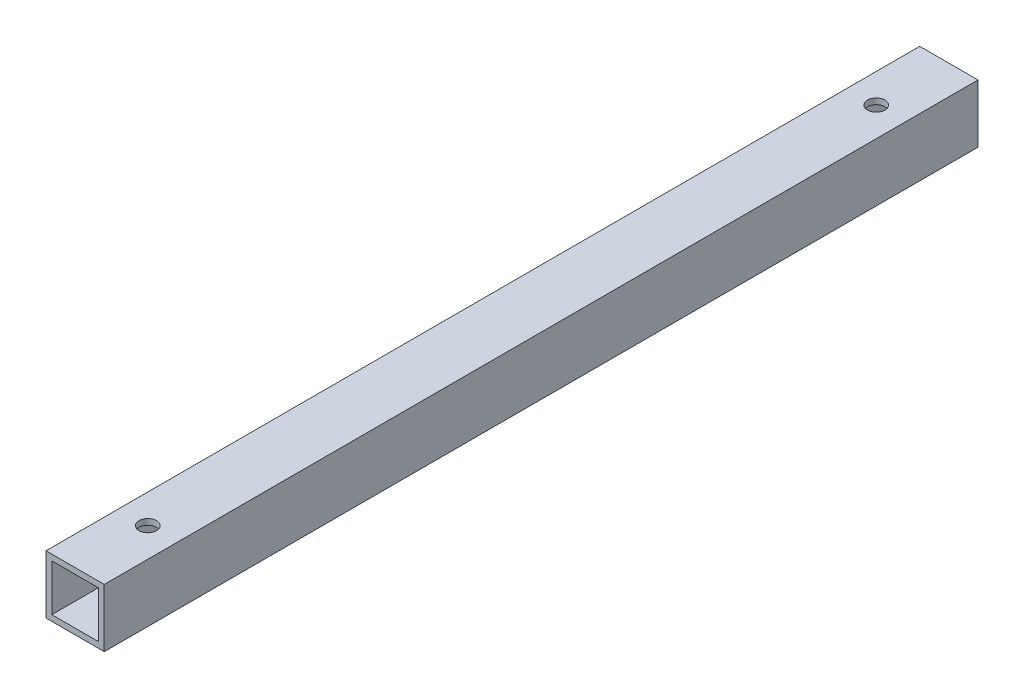
SolidWorks part; units mm, degrees
material "Thornel Mat VMA"
ref_plane "前视基准面" through (0, 0, 0) normal (0, 0, 1) x (1, 0, 0)
ref_plane "上视基准面" through (0, 0, 0) normal (0, 1, 0) x (1, 0, 0)
ref_plane "右视基准面" through (0, 0, 0) normal (1, 0, 0) x (0, 0, -1)
sketch "草图1" plane through (0, 0, 0) normal (0, 0, 1) x (1, 0, 0)
  line L1 (5, 5) -> (-5, 5)
  line L2 (5, 5) -> (5, -5)
  line L3 (5, -5) -> (-5, -5)
  line L4 (-5, 5) -> (-5, -5)
  line L5 (5, 5) -> (-5, -5) construction
  line L6 (5, -5) -> (-5, 5) construction
  line L7 (4, 4) -> (-4, 4)
  line L8 (4, 4) -> (4, -4)
  line L9 (4, -4) -> (-4, -4)
  line L10 (-4, 4) -> (-4, -4)
  line L11 (4, 4) -> (-4, -4) construction
  line L12 (4, -4) -> (-4, 4) construction
  point P0 (0, 0)
  point P6 (0, 0)
  dimension "D1" = 10
  dimension "D2" = 1
extrude "凸台-拉伸1" add sketch "草图1" along normal mid plane 150
hole_wizard "孔1" positions "草图2" profile "草图3" legacy end condition through all
sketch "草图2" plane through (0, -5, 0) normal (0, -1, 0) x (-1, 0, 0)
  point P0 (-0.0016, -62.5223)
  point P3 (-0.0016, 62.5296)
sketch "草图3" plane through (0.0016, -5, 62.5223) normal (1, 0, 0) x (0, 0, -1)
  line L0 (0, 0) -> (0, 10)
  line L1 (0, 10) -> (1.5, 10)
  line L2 (1.5, 10) -> (1.5, 0)
  line L3 (1.5, 0) -> (0, 0)
  line L4 (0, 110) -> (0, -10) construction
  dimension "直径" = 3
  dimension "深度" = 10
